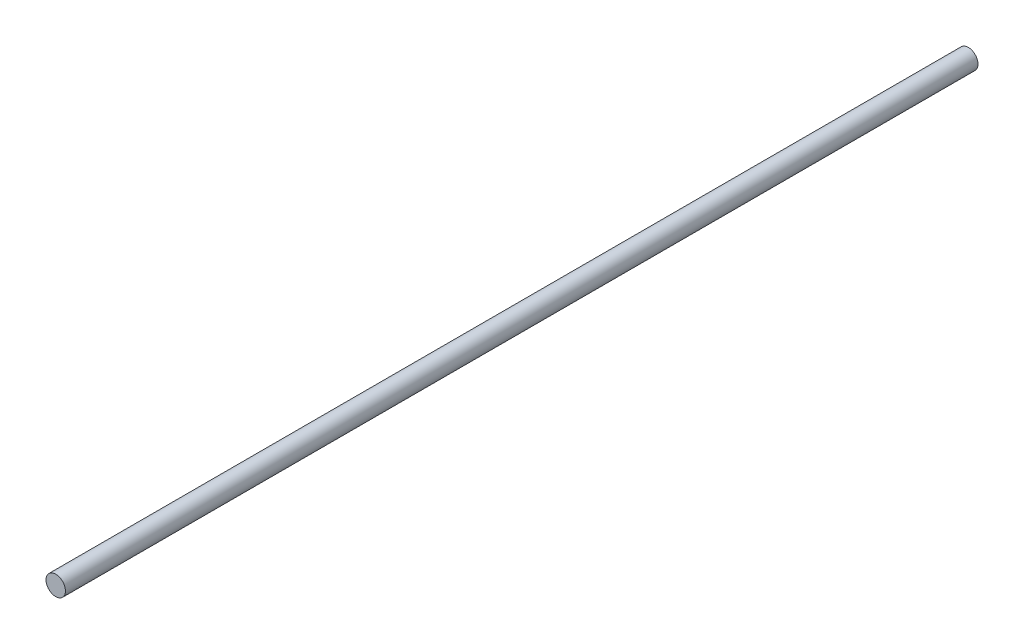
SolidWorks part; units mm, degrees
material "合金钢"
ref_plane "前视基准面" through (0, 0, 0) normal (0, 0, 1) x (1, 0, 0)
ref_plane "上视基准面" through (0, 0, 0) normal (0, 1, 0) x (1, 0, 0)
ref_plane "右视基准面" through (0, 0, 0) normal (1, 0, 0) x (0, 0, -1)
sketch "草图1" plane through (0, 0, 0) normal (0, 0, 1) x (1, 0, 0)
  circle A0 centre (0, 0) radius 4
  point P4 (0, 0)
  dimension "D1" = 8
extrude "凸台-拉伸1" add sketch "草图1" along normal blind 375
